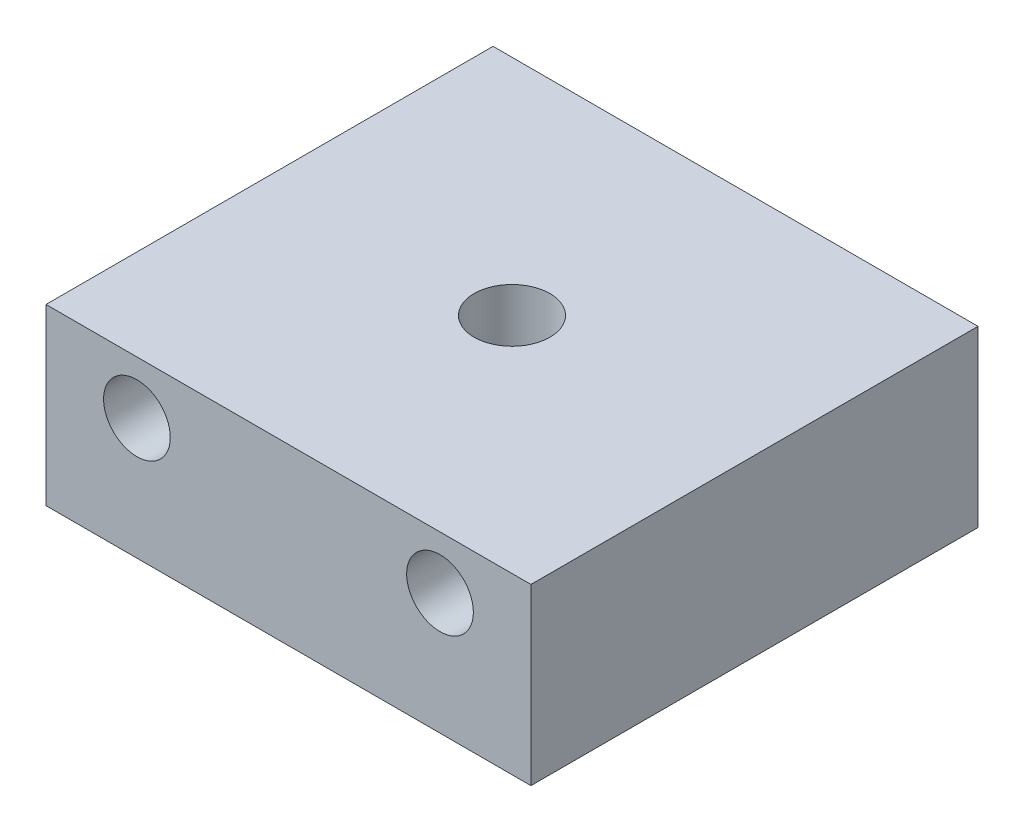
SolidWorks part; units mm, degrees
ref_plane "前视基准面" through (0, 0, 0) normal (0, 0, 1) x (1, 0, 0)
ref_plane "上视基准面" through (0, 0, 0) normal (0, 1, 0) x (1, 0, 0)
ref_plane "右视基准面" through (0, 0, 0) normal (1, 0, 0) x (0, 0, -1)
sketch "草图1" plane through (0, 0, 0) normal (0, 0, 1) x (1, 0, 0)
  line L0 (163, -49.74) -> (-23.7584, -49.74) construction
  line L1 (2, -49.74) -> (34, -49.74)
  line L2 (2, -49.74) -> (2, -38.24)
  line L3 (2, -38.24) -> (34, -38.24)
  line L4 (34, -49.74) -> (34, -38.24)
  circle A0 centre (8, -41.74) radius 2.2
  circle A1 centre (28, -41.7379) radius 2.2
  dimension "D1" = 6
  dimension "D4" = 4.4
  dimension "D5" = 4.4
  dimension "D2" = 6
  dimension "D3" = 3.5
extrude "凸台-拉伸1" add sketch "草图1" along normal blind 29.5
sketch "草图2" plane through (0, -49.74, 0) normal (0, -1, 0) x (1, 0, 0)
  line L0 (2, 29.5) -> (34, 0) construction
  line L1 (34, 29.5) -> (2, 0) construction
  circle A0 centre (18, 14.75) radius 2.5
  dimension "D1" = 5
extrude "切除-拉伸1" cut sketch "草图2" against normal blind 29.5
